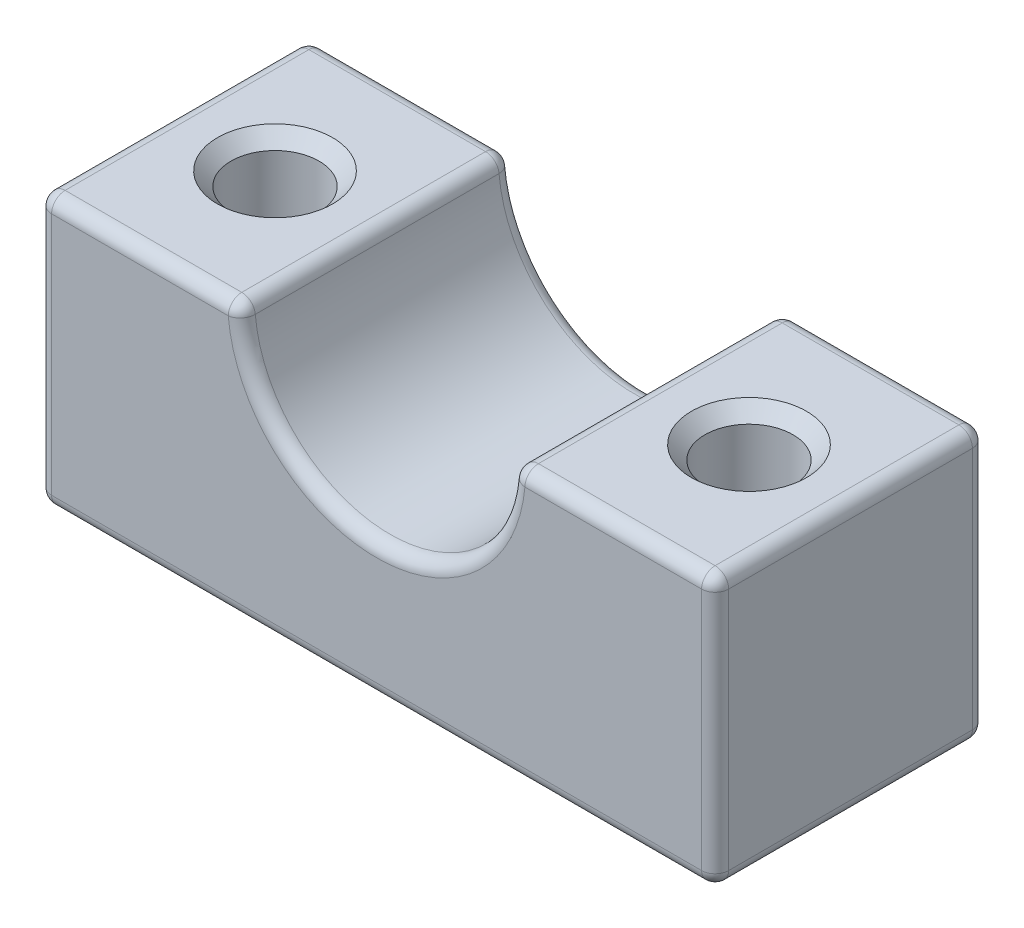
SolidWorks part; units mm, degrees
ref_plane "Płaszczyzna przednia" through (0, 0, 0) normal (0, 0, 1) x (1, 0, 0)
ref_plane "Płaszczyzna górna" through (0, 0, 0) normal (0, 1, 0) x (1, 0, 0)
ref_plane "Płaszczyzna prawa" through (0, 0, 0) normal (1, 0, 0) x (0, 0, -1)
sketch "Szkic1" plane through (0, 0, 0) normal (0, 0, 1) x (1, 0, 0)
  line L0 (-50, 0) -> (50, 0)
  line L1 (-50, -40) -> (50, -40)
  line L2 (-50, -40) -> (-50, 40)
  line L3 (-50, 40) -> (50, 40)
  line L4 (50, -40) -> (50, 40)
  line L5 (-50, -40) -> (50, 40) construction
  line L6 (-50, 40) -> (50, -40) construction
  circle A0 centre (0, 0) radius 20
  point P0 (0, 0)
  dimension "D1" = 40
  dimension "D2" = 40
  dimension "D3" = 100
extrude "Dodanie-wyciągnięcie1" add sketch "Szkic1" along normal blind 40 contours A0 L0 L2 L1 L4
sketch "Szkic2" plane through (0, 0, 0) normal (0, 1, 0) x (1, 0, 0)
  line L0 (-35, 0) -> (-35, -40) construction
  line L1 (-50, 0) -> (-20, 0) construction
  line L2 (-50, -40) -> (-20, -40) construction
  line L3 (35, 0) -> (35, -40) construction
  line L4 (20, 0) -> (50, 0) construction
  line L5 (20, -40) -> (50, -40) construction
  circle A0 centre (-35, -20) radius 6.5
  circle A1 centre (-35, -20) radius 6.5
  circle A2 centre (35, -20) radius 6.5
  circle A3 centre (35, -20) radius 6.5
  dimension "D1" = 13
  dimension "D2" = 20
  dimension "D3" = 20
sketch "Szkic3" plane through (0, -40, 0) normal (0, -1, 0) x (-1, 0, 0)
  line L0 (50, -40) -> (-50, -40) construction
  line L2 (-50, -40) -> (-50, 0) construction
  circle A0 centre (0, -30) radius 5
  dimension "D3" = 10
  dimension "D1" = 50
  dimension "D2" = 10
extrude "Wytnij-wyciągnięcie3" cut sketch "Szkic2" against normal up to next contours A0 | A2
extrude "Wytnij-wyciągnięcie6" cut sketch "Szkic3" against normal blind 15
chamfer "Sfazowanie1" distance 2 angle 45 5 edges at (-41.5, -40, 20) (-35, 0, 26.5) (28.5, -40, 20) (35, 0, 26.5) (0, -40, 25)
fillet "Zaokrąglenie1" radius 2 18 edges at (-20, 0, 20) (20, 0, 20) (-50, 0, 20) (-50, -40, 20) (-35, 0, 0) (-50, -20, 0) (0, -40, 0) (35, 0, 0) (0, -20, 0) (50, -40, 20) (50, 0, 20) (50, -20, 0) (35, 0, 40) (50, -20, 40) (0, -40, 40) (-50, -20, 40) (-35, 0, 40) (0, -20, 40)
